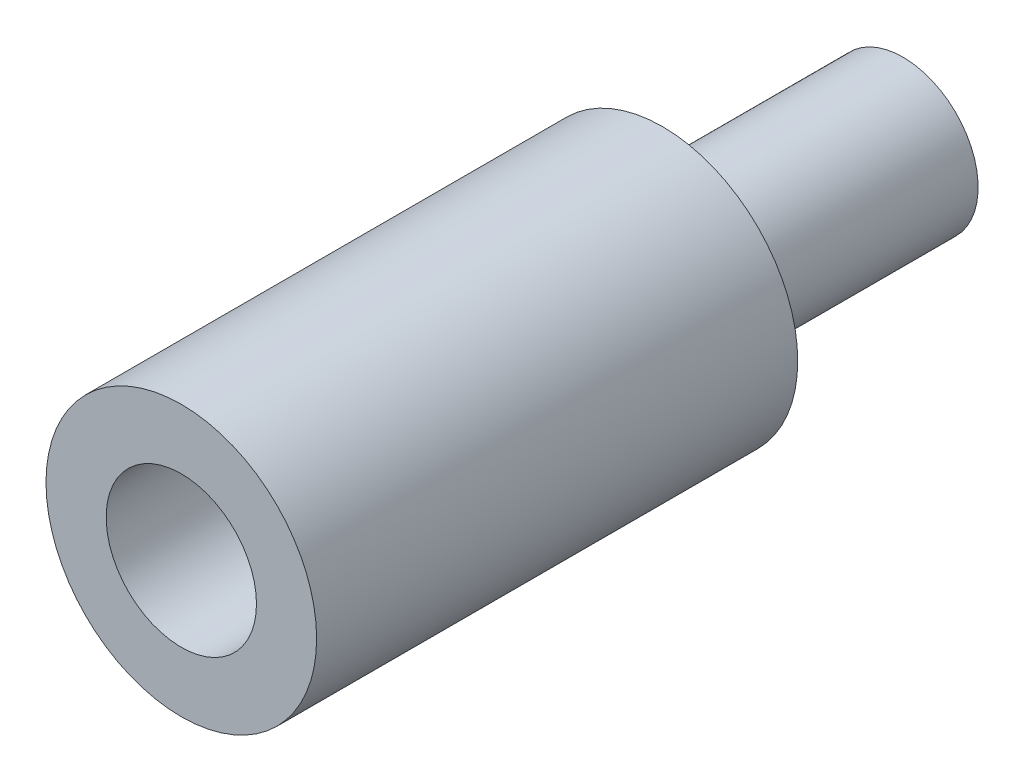
SolidWorks part; units mm, degrees
ref_plane "前视基准面" through (0, 0, 0) normal (0, 0, 1) x (1, 0, 0)
ref_plane "上视基准面" through (0, 0, 0) normal (0, 1, 0) x (1, 0, 0)
ref_plane "右视基准面" through (0, 0, 0) normal (1, 0, 0) x (0, 0, -1)
other "Configuration Table"
sketch "草图1" plane through (0, 0, 0) normal (0, 0, 1) x (1, 0, 0)
  circle A0 centre (0, 0) radius 2.25
  dimension "D1" = 4.5
extrude "凸台-拉伸1" add sketch "草图1" along normal blind 8
sketch "草图2" plane through (0, 0, 8) normal (0, 0, 1) x (1, 0, 0)
  circle A0 centre (0, 0) radius 1.25
  dimension "D1" = 2.5
extrude "切除-拉伸1" cut sketch "草图2" against normal blind 15
sketch "草图3" plane through (0, 0, 0) normal (0, 0, -1) x (-1, 0, 0)
  circle A0 centre (0, 0) radius 1.25
  dimension "D1" = 2.5
extrude "凸台-拉伸2" add sketch "草图3" along normal blind 4 contours A0
